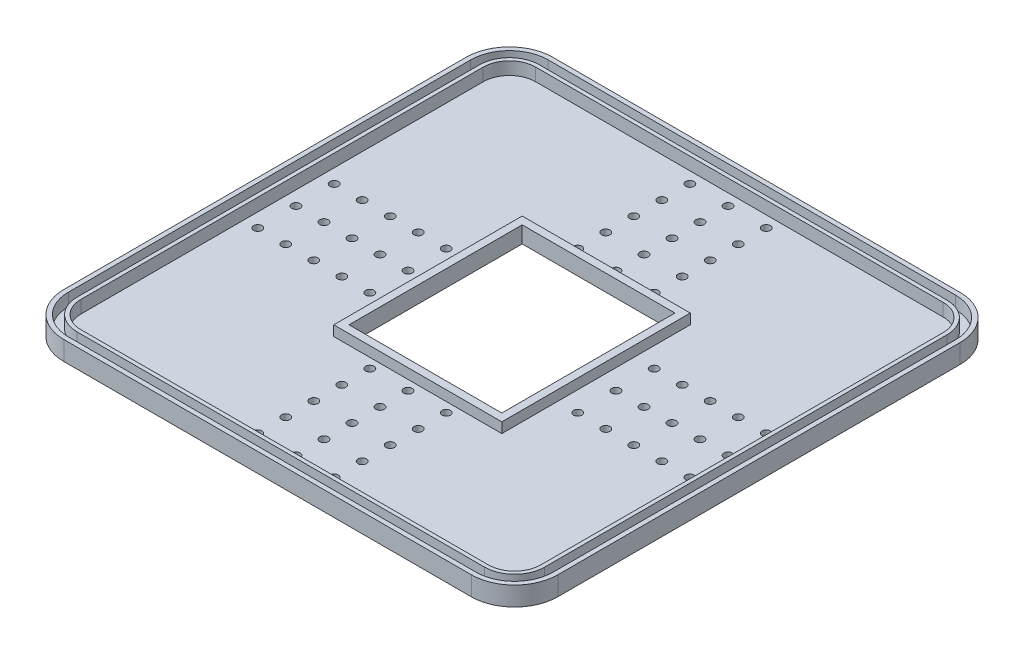
SolidWorks part; units mm, degrees
ref_plane "Front Plane" through (0, 0, 0) normal (0, 0, 1) x (1, 0, 0)
ref_plane "Top Plane" through (0, 0, 0) normal (0, 1, 0) x (1, 0, 0)
ref_plane "Right Plane" through (0, 0, 0) normal (1, 0, 0) x (0, 0, -1)
sketch "Sketch1" plane through (0, 0, 0) normal (0, 1, 0) x (1, 0, 0)
  line L0 (-97, -79) -> (-97, 79)
  line L1 (-80, -94) -> (80, -94)
  line L2 (-95, -79) -> (-95, 79)
  line L3 (-80, 94) -> (80, 94)
  line L4 (95, -79) -> (95, 79)
  line L5 (-95, -94) -> (95, 94) construction
  line L6 (-95, 94) -> (95, -94) construction
  line L7 (-80, 96) -> (80, 96)
  line L8 (97, -79) -> (97, 79)
  line L9 (-80, -96) -> (80, -96)
  arc A0 (-80, -94) -> (-95, -79) centre (-80, -79) cw
  arc A1 (80, -94) -> (95, -79) centre (80, -79) ccw
  arc A2 (80, 94) -> (95, 79) centre (80, 79) cw
  arc A3 (-95, 79) -> (-80, 94) centre (-80, 79) cw
  arc A4 (-97, 79) -> (-80, 96) centre (-80, 79) cw
  arc A5 (80, 96) -> (97, 79) centre (80, 79) cw
  arc A6 (80, -96) -> (97, -79) centre (80, -79) ccw
  arc A7 (-80, -96) -> (-97, -79) centre (-80, -79) cw
  point P0 (0, 0)
  dimension "D1" = 190
  dimension "D3" = 15
  dimension "D2" = 188
  dimension "D4" = 2
extrude "Boss-Extrude1" add sketch "Sketch1" along normal blind 2.5 contours A3 L2 A0 L1 A1 L4 A2 L3 | A7 L9 A6 L8 A5 L7 A4 L0 L2 A3 L3 A2 L4 A1 L1 A0
sketch "Sketch3" plane through (0, 2.5, 0) normal (0, 1, 0) x (1, 0, 0)
  line L0 (80, 91) -> (-80, 91) construction
  line L1 (-92, 79) -> (-92, -79) construction
  line L2 (-80, -91) -> (80, -91) construction
  line L3 (92, -79) -> (92, 79) construction
  line L4 (80, 94) -> (-80, 94)
  line L5 (95, -79) -> (95, 79)
  line L6 (-80, -94) -> (80, -94)
  line L7 (-95, 79) -> (-95, -79)
  line L8 (80, 94) -> (-80, 94) construction
  line L9 (95, -79) -> (95, 79) construction
  line L10 (-80, -94) -> (80, -94) construction
  line L11 (-95, 79) -> (-95, -79) construction
  line L12 (-97, 79) -> (-97, -79)
  line L13 (80, 96) -> (-80, 96)
  line L14 (97, -79) -> (97, 79)
  line L15 (-80, -96) -> (80, -96)
  line L16 (-97, 79) -> (-97, -79)
  line L17 (80, 96) -> (-80, 96)
  line L18 (97, -79) -> (97, 79)
  line L19 (-80, -96) -> (80, -96)
  line L20 (-80, -94.2) -> (80, -94.2)
  line L21 (95.2, -79) -> (95.2, 79)
  line L22 (80, 94.2) -> (-80, 94.2)
  line L23 (-95.2, 79) -> (-95.2, -79)
  line L24 (-80, -90.8) -> (80, -90.8)
  line L25 (91.8, -79) -> (91.8, 79)
  line L26 (80, 90.8) -> (-80, 90.8)
  line L27 (-91.8, 79) -> (-91.8, -79)
  line L28 (-80, -89.3) -> (80, -89.3)
  line L29 (90.3, -79) -> (90.3, 79)
  line L30 (80, 89.3) -> (-80, 89.3)
  line L31 (-90.3, 79) -> (-90.3, -79)
  arc A0 (-80, 91) -> (-92, 79) centre (-80, 79) ccw construction
  arc A1 (-92, -79) -> (-80, -91) centre (-80, -79) ccw construction
  arc A2 (80, -91) -> (92, -79) centre (80, -79) ccw construction
  arc A3 (92, 79) -> (80, 91) centre (80, 79) ccw construction
  arc A4 (95, 79) -> (80, 94) centre (80, 79) ccw
  arc A5 (80, -94) -> (95, -79) centre (80, -79) ccw
  arc A6 (-95, -79) -> (-80, -94) centre (-80, -79) ccw
  arc A7 (-80, 94) -> (-95, 79) centre (-80, 79) ccw
  arc A8 (95, 79) -> (80, 94) centre (80, 79) ccw construction
  arc A9 (80, -94) -> (95, -79) centre (80, -79) ccw construction
  arc A10 (-95, -79) -> (-80, -94) centre (-80, -79) ccw construction
  arc A11 (-80, 94) -> (-95, 79) centre (-80, 79) ccw construction
  arc A12 (-80, 96) -> (-97, 79) centre (-80, 79) ccw
  arc A13 (97, 79) -> (80, 96) centre (80, 79) ccw
  arc A14 (80, -96) -> (97, -79) centre (80, -79) ccw
  arc A15 (-97, -79) -> (-80, -96) centre (-80, -79) ccw
  arc A16 (-80, 96) -> (-97, 79) centre (-80, 79) ccw
  arc A17 (97, 79) -> (80, 96) centre (80, 79) ccw
  arc A18 (80, -96) -> (97, -79) centre (80, -79) ccw
  arc A19 (-97, -79) -> (-80, -96) centre (-80, -79) ccw
  arc A20 (80, -94.2) -> (95.2, -79) centre (80, -79) ccw
  arc A21 (95.2, 79) -> (80, 94.2) centre (80, 79) ccw
  arc A22 (-80, 94.2) -> (-95.2, 79) centre (-80, 79) ccw
  arc A23 (-95.2, -79) -> (-80, -94.2) centre (-80, -79) ccw
  arc A24 (80, -90.8) -> (91.8, -79) centre (80, -79) ccw
  arc A25 (91.8, 79) -> (80, 90.8) centre (80, 79) ccw
  arc A26 (-80, 90.8) -> (-91.8, 79) centre (-80, 79) ccw
  arc A27 (-91.8, -79) -> (-80, -90.8) centre (-80, -79) ccw
  arc A28 (-90.3, -79) -> (-80, -89.3) centre (-80, -79) ccw
  arc A29 (80, -89.3) -> (90.3, -79) centre (80, -79) ccw
  arc A30 (90.3, 79) -> (80, 89.3) centre (80, 79) ccw
  arc A31 (-80, 89.3) -> (-90.3, 79) centre (-80, 79) ccw
  arc M17 (-97, -79) -> (-80, -96) centre (-80, -79) ccw
  line M18 (-80, -96) -> (80, -96)
  arc M19 (80, -96) -> (97, -79) centre (80, -79) ccw
  line M20 (97, -79) -> (97, 79)
  arc M21 (97, 79) -> (80, 96) centre (80, 79) ccw
  line M22 (80, 96) -> (-80, 96)
  arc M23 (-80, 96) -> (-97, 79) centre (-80, 79) ccw
  line M24 (-97, 79) -> (-97, -79)
  dimension "D1" = 0
  dimension "D2" = 0
  dimension "D3" = 3
  dimension "D4" = 0.2
  dimension "D5" = 0.2
  dimension "D6" = 1.5
extrude "Boss-Extrude2" add sketch "Sketch3" along normal blind 5 contours L27 A27 L24 A24 L25 A25 L26 A26 A31 L30 A30 L29 A29 L28 A28 L31 | A23 L23 A22 L22 A21 L21 A20 L20 M24 M17 M18 M19 M20 M21 M22 M23
sketch "Sketch4" plane through (0, 2.5, 0) normal (0, 1, 0) x (1, 0, 0)
  line L1 (-30, -34) -> (30, -34)
  line L2 (-30, -34) -> (-30, 34)
  line L3 (-30, 34) -> (30, 34)
  line L4 (30, -34) -> (30, 34)
  line L5 (-30, -34) -> (30, 34) construction
  line L6 (-30, 34) -> (30, -34) construction
  point P0 (0, 0)
  dimension "D1" = 60
  dimension "D2" = 68
extrude "Cut-Extrude1" cut sketch "Sketch4" against normal blind 5
sketch "Sketch5" plane through (0, 2.5, 0) normal (0, 1, 0) x (1, 0, 0)
  line L0 (97, -67.5155) -> (69.9375, -67.5155)
  line L1 (97, -79) -> (97, 79) construction
  line L2 (69.9375, -67.5155) -> (69.9375, -96)
  line L3 (-80, -96) -> (80, -96) construction
  line L4 (69.9375, -96) -> (80, -96)
  line L5 (97, -67.5155) -> (97, -79)
  line L10 (80, 94) -> (-80, 94)
  line L11 (95, -79) -> (95, 79)
  line L12 (-80, -94) -> (80, -94)
  line L13 (-95, 79) -> (-95, -79)
  line L14 (80, 94) -> (-80, 94)
  line L15 (95, -79) -> (95, 79)
  line L16 (-80, -94) -> (80, -94)
  line L17 (-95, 79) -> (-95, -79)
  line L18 (-97, 79) -> (-97, -79)
  line L19 (80, 96) -> (-80, 96)
  line L20 (97, -79) -> (97, 79)
  line L21 (-80, -96) -> (80, -96)
  line L22 (-97, 79) -> (-97, -79)
  line L23 (80, 96) -> (-80, 96)
  line L24 (97, -79) -> (97, 79)
  line L25 (-80, -96) -> (80, -96)
  arc A0 (80, -96) -> (97, -79) centre (80, -79) ccw construction
  arc A1 (80, -96) -> (97, -79) centre (80, -79) ccw
  arc A6 (95, 79) -> (80, 94) centre (80, 79) ccw
  arc A7 (80, -94) -> (95, -79) centre (80, -79) ccw
  arc A8 (-95, -79) -> (-80, -94) centre (-80, -79) ccw
  arc A9 (-80, 94) -> (-95, 79) centre (-80, 79) ccw
  arc A10 (95, 79) -> (80, 94) centre (80, 79) ccw
  arc A11 (80, -94) -> (95, -79) centre (80, -79) ccw
  arc A12 (-95, -79) -> (-80, -94) centre (-80, -79) ccw
  arc A13 (-80, 94) -> (-95, 79) centre (-80, 79) ccw
  arc A14 (-80, 96) -> (-97, 79) centre (-80, 79) ccw
  arc A15 (97, 79) -> (80, 96) centre (80, 79) ccw
  arc A16 (80, -96) -> (97, -79) centre (80, -79) ccw
  arc A17 (-97, -79) -> (-80, -96) centre (-80, -79) ccw
  arc A18 (-80, 96) -> (-97, 79) centre (-80, 79) ccw
  arc A19 (97, 79) -> (80, 96) centre (80, 79) ccw
  arc A20 (80, -96) -> (97, -79) centre (80, -79) ccw
  arc A21 (-97, -79) -> (-80, -96) centre (-80, -79) ccw
  dimension "D1" = 0
  dimension "D2" = 0
extrude "Cut-Extrude2" [suppressed] cut sketch "Sketch5" against normal up to next and the other way up to next contours L14 A13 L17 A12 L16 L2 A21 L25 A20 L24 L3 L1 L0 L15 A10 | L22 A21 L25 L2 L16 A12 L17 A13 L14 A10 L15 L0 L24 A19 L23 A18 | L2 L0 L1 L3 L24 A20 L25 A21 A19 L22 A18 L23 | L0 L2 A21 L1
sketch "Sketch6" plane through (0, 2.5, 0) normal (0, 1, 0) x (1, 0, 0)
  line L0 (30, 34) -> (-30, 34) construction
  line L1 (30, 34) -> (-30, 34)
  line L2 (-30, 34) -> (-30, -34) construction
  line L3 (-30, 34) -> (-30, -34)
  line L4 (-90.3, 79) -> (-90.3, -79)
  line L5 (-80, -89.3) -> (80, -89.3)
  line L6 (90.3, -79) -> (90.3, 79)
  line L7 (80, 89.3) -> (-80, 89.3)
  line L8 (-90.3, 79) -> (-90.3, -79)
  line L9 (-80, -89.3) -> (80, -89.3)
  line L10 (90.3, -79) -> (90.3, 79)
  line L11 (80, 89.3) -> (-80, 89.3)
  line L12 (-30, -34) -> (30, -34) construction
  line L13 (-30, -34) -> (30, -34)
  line L14 (30, -34) -> (30, 34) construction
  line L15 (30, -34) -> (30, 34)
  line L16 (33, 37) -> (-33, 37)
  line L17 (-33, 37) -> (-33, -37)
  line L18 (-33, -37) -> (33, -37)
  line L19 (33, -37) -> (33, 37)
  arc A4 (-80, 89.3) -> (-90.3, 79) centre (-80, 79) ccw
  arc A5 (-90.3, -79) -> (-80, -89.3) centre (-80, -79) ccw
  arc A6 (80, -89.3) -> (90.3, -79) centre (80, -79) ccw
  arc A7 (90.3, 79) -> (80, 89.3) centre (80, 79) ccw
  arc A8 (-80, 89.3) -> (-90.3, 79) centre (-80, 79) ccw
  arc A9 (-90.3, -79) -> (-80, -89.3) centre (-80, -79) ccw
  arc A10 (80, -89.3) -> (90.3, -79) centre (80, -79) ccw
  arc A11 (90.3, 79) -> (80, 89.3) centre (80, 79) ccw
  line M9 (30, 34) -> (30, -34)
  line M10 (30, -34) -> (-30, -34)
  line M11 (-30, -34) -> (-30, 34)
  line M12 (-30, 34) -> (30, 34)
  dimension "D1" = 0
  dimension "D2" = 3
extrude "Boss-Extrude3" add sketch "Sketch6" along normal blind 4 contours L18 L19 L16 L17 M12 M9 M10 M11
sketch "Sketch7" plane through (0, 2.5, 0) normal (0, 1, 0) x (1, 0, 0)
  line L0 (-40.8346, 0) -> (-51.8346, 0) construction
  line L1 (-51.8346, 0) -> (-62.8346, 0) construction
  line L2 (-62.8346, 0) -> (-73.8346, 0) construction
  line L3 (-73.8346, 0) -> (-84.8346, 0) construction
  line L4 (-40.8346, 15) -> (-51.8346, 15) construction
  line L5 (-51.8346, 15) -> (-62.8346, 15) construction
  line L6 (-62.8346, 15) -> (-73.8346, 15) construction
  line L7 (-73.8346, 15) -> (-84.8346, 15) construction
  line L8 (-40.8346, -15) -> (-51.8346, -15) construction
  line L9 (-51.8346, -15) -> (-62.8346, -15) construction
  line L10 (-62.8346, -15) -> (-73.8346, -15) construction
  line L11 (-73.8346, -15) -> (-84.8346, -15) construction
  line L12 (0, 40.8346) -> (0, 51.8346) construction
  line L13 (0, 51.8346) -> (0, 62.8346) construction
  line L14 (0, 62.8346) -> (0, 73.8346) construction
  line L15 (0, 73.8346) -> (0, 84.8346) construction
  line L16 (15, 40.8346) -> (15, 51.8346) construction
  line L17 (15, 51.8346) -> (15, 62.8346) construction
  line L18 (15, 62.8346) -> (15, 73.8346) construction
  line L19 (15, 73.8346) -> (15, 84.8346) construction
  line L20 (-15, 40.8346) -> (-15, 51.8346) construction
  line L21 (-15, 51.8346) -> (-15, 62.8346) construction
  line L22 (-15, 62.8346) -> (-15, 73.8346) construction
  line L23 (-15, 73.8346) -> (-15, 84.8346) construction
  line L24 (40.8346, 0) -> (51.8346, 0) construction
  line L25 (51.8346, 0) -> (62.8346, 0) construction
  line L26 (62.8346, 0) -> (73.8346, 0) construction
  line L27 (73.8346, 0) -> (84.8346, 0) construction
  line L28 (40.8346, -15) -> (51.8346, -15) construction
  line L29 (51.8346, -15) -> (62.8346, -15) construction
  line L30 (62.8346, -15) -> (73.8346, -15) construction
  line L31 (73.8346, -15) -> (84.8346, -15) construction
  line L32 (40.8346, 15) -> (51.8346, 15) construction
  line L33 (51.8346, 15) -> (62.8346, 15) construction
  line L34 (62.8346, 15) -> (73.8346, 15) construction
  line L35 (73.8346, 15) -> (84.8346, 15) construction
  line L36 (0, -40.8346) -> (0, -51.8346) construction
  line L37 (0, -51.8346) -> (0, -62.8346) construction
  line L38 (0, -62.8346) -> (0, -73.8346) construction
  line L39 (0, -73.8346) -> (0, -84.8346) construction
  line L40 (-15, -40.8346) -> (-15, -51.8346) construction
  line L41 (-15, -51.8346) -> (-15, -62.8346) construction
  line L42 (-15, -62.8346) -> (-15, -73.8346) construction
  line L43 (-15, -73.8346) -> (-15, -84.8346) construction
  line L44 (15, -40.8346) -> (15, -51.8346) construction
  line L45 (15, -51.8346) -> (15, -62.8346) construction
  line L46 (15, -62.8346) -> (15, -73.8346) construction
  line L47 (15, -73.8346) -> (15, -84.8346) construction
  circle A0 centre (-84.8346, 15) radius 1.65
  circle A1 centre (-73.8346, 15) radius 1.65
  circle A2 centre (-62.8346, 15) radius 1.65
  circle A3 centre (-51.8346, 15) radius 1.65
  circle A4 centre (-40.8346, 15) radius 1.65
  circle A5 centre (-40.8346, 0) radius 1.65
  circle A6 centre (-51.8346, 0) radius 1.65
  circle A7 centre (-62.8346, 0) radius 1.65
  circle A8 centre (-73.8346, 0) radius 1.65
  circle A9 centre (-84.8346, 0) radius 1.65
  circle A10 centre (-84.8346, -15) radius 1.65
  circle A11 centre (-73.8346, -15) radius 1.65
  circle A12 centre (-62.8346, -15) radius 1.65
  circle A14 centre (-51.8346, -15) radius 1.65
  circle A15 centre (-40.8346, -15) radius 1.65
  circle A16 centre (15, 84.8346) radius 1.65
  circle A17 centre (15, 73.8346) radius 1.65
  circle A18 centre (15, 62.8346) radius 1.65
  circle A19 centre (15, 51.8346) radius 1.65
  circle A20 centre (15, 40.8346) radius 1.65
  circle A21 centre (0, 40.8346) radius 1.65
  circle A22 centre (0, 51.8346) radius 1.65
  circle A23 centre (0, 62.8346) radius 1.65
  circle A24 centre (0, 73.8346) radius 1.65
  circle A25 centre (0, 84.8346) radius 1.65
  circle A26 centre (-15, 84.8346) radius 1.65
  circle A27 centre (-15, 73.8346) radius 1.65
  circle A28 centre (-15, 62.8346) radius 1.65
  circle A29 centre (-15, 51.8346) radius 1.65
  circle A30 centre (-15, 40.8346) radius 1.65
  circle A31 centre (84.8346, -15) radius 1.65
  circle A32 centre (73.8346, -15) radius 1.65
  circle A33 centre (62.8346, -15) radius 1.65
  circle A34 centre (51.8346, -15) radius 1.65
  circle A35 centre (40.8346, -15) radius 1.65
  circle A36 centre (40.8346, 0) radius 1.65
  circle A37 centre (51.8346, 0) radius 1.65
  circle A38 centre (62.8346, 0) radius 1.65
  circle A39 centre (73.8346, 0) radius 1.65
  circle A40 centre (84.8346, 0) radius 1.65
  circle A41 centre (84.8346, 15) radius 1.65
  circle A42 centre (73.8346, 15) radius 1.65
  circle A43 centre (62.8346, 15) radius 1.65
  circle A44 centre (51.8346, 15) radius 1.65
  circle A45 centre (40.8346, 15) radius 1.65
  circle A46 centre (-15, -84.8346) radius 1.65
  circle A47 centre (-15, -73.8346) radius 1.65
  circle A48 centre (-15, -62.8346) radius 1.65
  circle A49 centre (-15, -51.8346) radius 1.65
  circle A50 centre (-15, -40.8346) radius 1.65
  circle A51 centre (0, -40.8346) radius 1.65
  circle A52 centre (0, -51.8346) radius 1.65
  circle A53 centre (0, -62.8346) radius 1.65
  circle A54 centre (0, -73.8346) radius 1.65
  circle A55 centre (0, -84.8346) radius 1.65
  circle A56 centre (15, -84.8346) radius 1.65
  circle A57 centre (15, -73.8346) radius 1.65
  circle A58 centre (15, -62.8346) radius 1.65
  circle A59 centre (15, -51.8346) radius 1.65
  circle A60 centre (15, -40.8346) radius 1.65
  point P0 (-40.8346, 0)
  point P1 (-51.8346, 0)
  point P2 (-62.8346, 0)
  point P3 (-73.8346, 0)
  point P4 (-84.8346, 0)
  point P5 (-40.8346, 15)
  point P6 (-51.8346, 15)
  point P7 (-62.8346, 15)
  point P8 (-73.8346, 15)
  point P9 (-84.8346, 15)
  point P22 (-40.8346, -15)
  point P23 (-51.8346, -15)
  point P24 (-62.8346, -15)
  point P25 (-73.8346, -15)
  point P26 (-84.8346, -15)
  point P49 (0, 40.8346)
  point P50 (0, 51.8346)
  point P51 (0, 62.8346)
  point P52 (0, 73.8346)
  point P53 (0, 84.8346)
  point P54 (15, 40.8346)
  point P55 (15, 51.8346)
  point P56 (15, 62.8346)
  point P57 (15, 73.8346)
  point P58 (15, 84.8346)
  point P71 (-15, 40.8346)
  point P72 (-15, 51.8346)
  point P73 (-15, 62.8346)
  point P74 (-15, 73.8346)
  point P75 (-15, 84.8346)
  point P94 (40.8346, 0)
  point P95 (51.8346, 0)
  point P96 (62.8346, 0)
  point P97 (73.8346, 0)
  point P98 (84.8346, 0)
  point P99 (40.8346, -15)
  point P100 (51.8346, -15)
  point P101 (62.8346, -15)
  point P102 (73.8346, -15)
  point P103 (84.8346, -15)
  point P116 (40.8346, 15)
  point P117 (51.8346, 15)
  point P118 (62.8346, 15)
  point P119 (73.8346, 15)
  point P120 (84.8346, 15)
  point P139 (0, -40.8346)
  point P140 (0, -51.8346)
  point P141 (0, -62.8346)
  point P142 (0, -73.8346)
  point P143 (0, -84.8346)
  point P144 (-15, -40.8346)
  point P145 (-15, -51.8346)
  point P146 (-15, -62.8346)
  point P147 (-15, -73.8346)
  point P148 (-15, -84.8346)
  point P161 (15, -40.8346)
  point P162 (15, -51.8346)
  point P163 (15, -62.8346)
  point P164 (15, -73.8346)
  point P165 (15, -84.8346)
  point P184 (0, 0)
  dimension "D4" = 3.3
  dimension "D1" = 15
  dimension "D2" = 15
  dimension "D3" = 11
  dimension "D5" = 4
extrude "Cut-Extrude3" cut sketch "Sketch7" against normal up to next (2.5 mm away)
